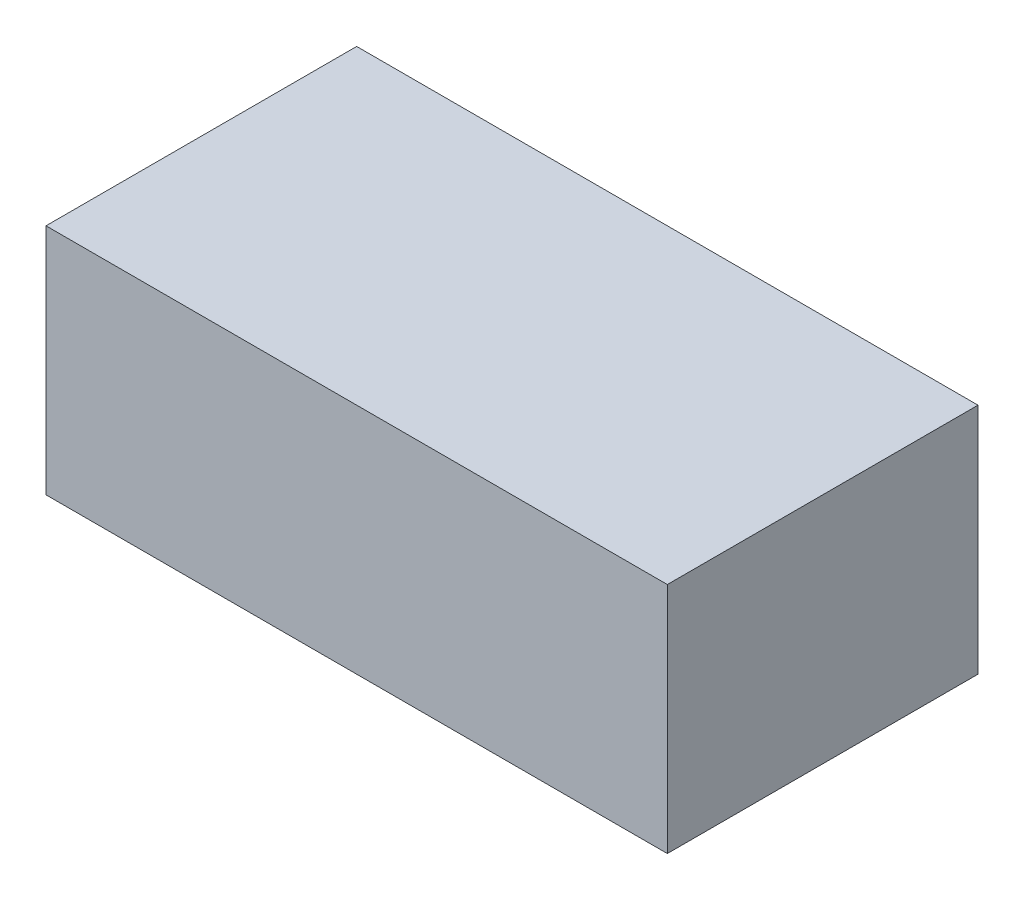
SolidWorks part; units mm, degrees
ref_plane "Front Plane" through (0, 0, 0) normal (0, 0, 1) x (1, 0, 0)
ref_plane "Top Plane" through (0, 0, 0) normal (0, 1, 0) x (1, 0, 0)
ref_plane "Right Plane" through (0, 0, 0) normal (1, 0, 0) x (0, 0, -1)
sketch "Sketch5" plane through (0, 0, 0) normal (0, 0, 1) x (1, 0, 0)
  line L1 (0, 0) -> (40, 0)
  line L2 (0, 0) -> (0, 15)
  line L3 (0, 15) -> (40, 15)
  line L4 (40, 0) -> (40, 15)
extrude "Boss-Extrude4" add sketch "Sketch5" along normal blind 20
